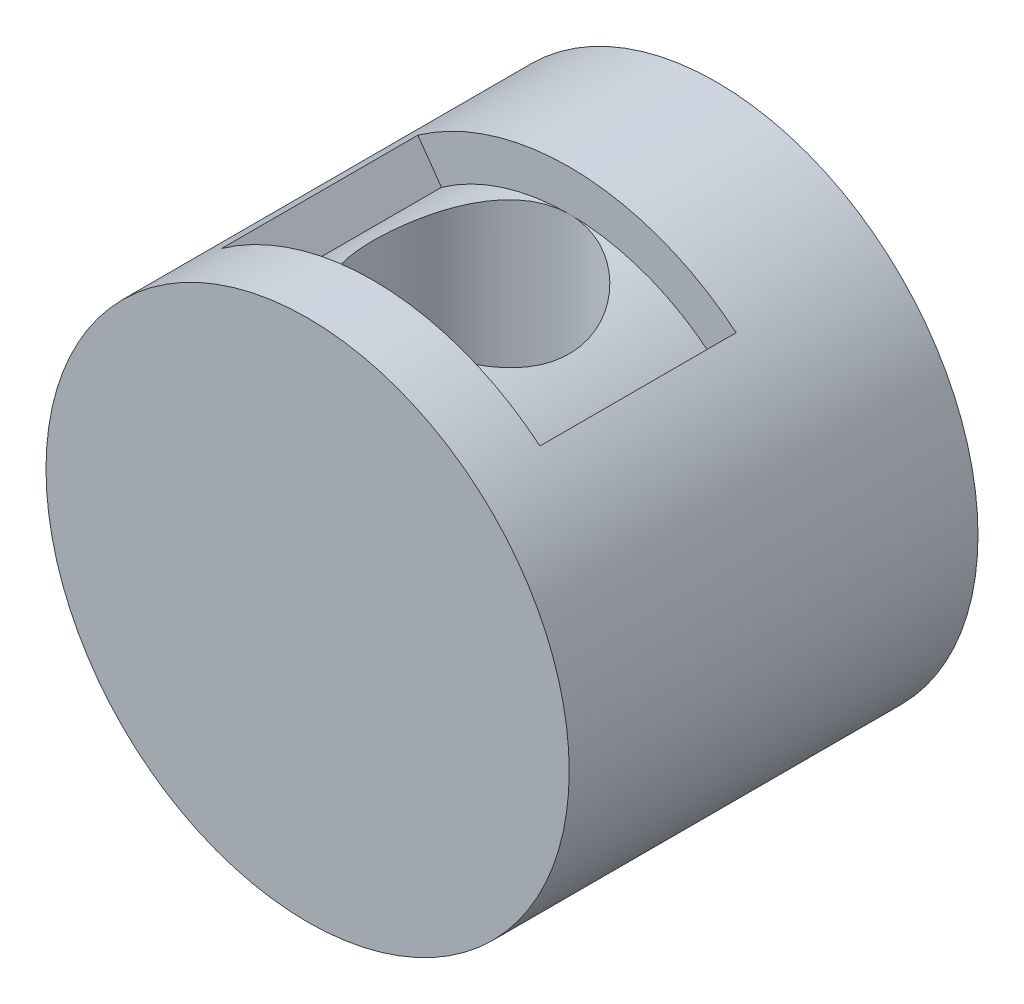
SolidWorks part; units mm, degrees
ref_plane "Front Plane" through (0, 0, 0) normal (0, 0, 1) x (1, 0, 0)
ref_plane "Top Plane" through (0, 0, 0) normal (0, 1, 0) x (1, 0, 0)
ref_plane "Right Plane" through (0, 0, 0) normal (1, 0, 0) x (0, 0, -1)
sketch "Sketch1" plane through (0, 0, 0) normal (0, 0, 1) x (1, 0, 0)
  circle A0 centre (0, 0) radius 16
  dimension "D1" = 32
extrude "Boss-Extrude1" add sketch "Sketch1" against normal blind 25
sketch "Sketch2" plane through (0, 0, 0) normal (0, 1, 0) x (1, 0, 0)
  circle A0 centre (0, 10) radius 6
  point P2 (0, 0)
  dimension "D1" = 12
  dimension "D2" = 10
extrude "Cut-Extrude1" cut sketch "Sketch2" against normal through all both and the other way through all
sketch "Sketch3" plane through (0, 0, 0) normal (0, 0, 1) x (1, 0, 0)
  line L0 (0, 0) -> (0.5983, 15.9888) construction
  line L1 (-7.812, 11.0101) -> (-9.2587, 13.049)
  line L2 (8.6131, 10.3954) -> (10.2081, 12.3205)
  arc A0 (-9.2587, 13.049) -> (10.2081, 12.3205) centre (0, 0) cw
  circle A1 centre (0, 0) radius 16 construction
  arc A2 (-7.812, 11.0101) -> (8.6131, 10.3954) centre (0, 0) cw
  point P8 (0, 0)
  point P10 (0, 0)
  point P11 (0, 0)
  dimension "D1" = 13.5
  dimension "D2" = 75
extrude "Cut-Extrude2" cut sketch "Sketch3" against normal blind 12 from offset 4 offset against normal yes
